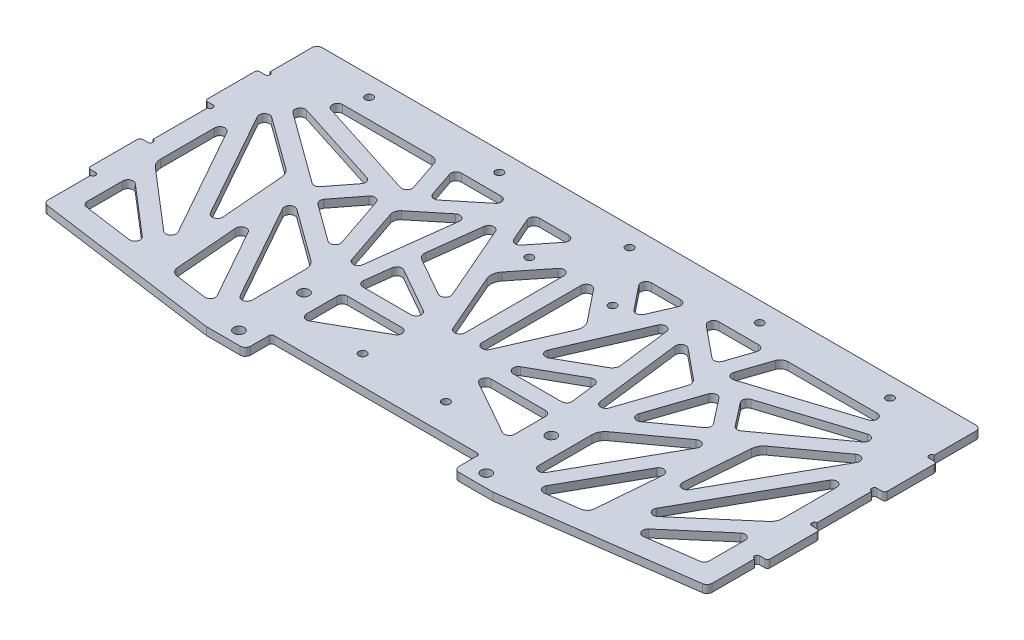
SolidWorks part; units mm, degrees
material "Thornel Mat VMA"
ref_plane "前视基准面" through (0, 0, 0) normal (0, 0, 1) x (1, 0, 0)
ref_plane "上视基准面" through (0, 0, 0) normal (0, 1, 0) x (1, 0, 0)
ref_plane "右视基准面" through (0, 0, 0) normal (1, 0, 0) x (0, 0, -1)
sketch "草图1" plane through (0, 0, 0) normal (0, 1, 0) x (1, 0, 0)
  line L0 (-47.5, 20) -> (-47.5, -10) construction
  line L1 (-55, -10) -> (-127.5, 0)
  line L3 (-55, -10) -> (-40, -10)
  line L5 (-127.5, 105) -> (127.5, 105)
  line L6 (-127.5, 85) -> (-127.5, 105)
  line L11 (0, -1.65) -> (0, 1.65) construction
  line L12 (55, -10) -> (40, -10)
  line L14 (130.5, 85) -> (130.5, 65)
  line L15 (127.5, 65) -> (130.5, 65)
  line L16 (127.5, 85) -> (130.5, 85)
  line L17 (127.5, 85) -> (127.5, 105)
  line L18 (127.5, 0) -> (127.5, 20)
  line L19 (55, -10) -> (127.5, 0)
  line L20 (-40, -10) -> (-40, 0)
  line L21 (-40, 0) -> (40, 0)
  line L22 (40, -10) -> (40, 0)
  line L23 (127.5, 40) -> (127.5, 65)
  line L24 (127.5, 40) -> (130.5, 40)
  line L26 (127.5, 20) -> (130.5, 20)
  line L27 (130.5, 40) -> (130.5, 20)
  line L28 (-127.5, 0) -> (-127.5, 20)
  line L29 (-130.5, 40) -> (-130.5, 20)
  line L30 (-127.5, 20) -> (-130.5, 20)
  line L31 (-127.5, 40) -> (-130.5, 40)
  line L32 (-127.5, 40) -> (-127.5, 65)
  line L33 (-127.5, 85) -> (-130.5, 85)
  line L34 (-127.5, 65) -> (-130.5, 65)
  line L35 (-130.5, 85) -> (-130.5, 65)
  line L37 (-16, 75) -> (16, 75) construction
  line L38 (-16, 75) -> (-16, 11) construction
  line L39 (-16, 11) -> (16, 11) construction
  line L40 (16, 75) -> (16, 11) construction
  circle A0 centre (-47.5, 20) radius 2
  circle A1 centre (-47.5, -5) radius 2
  circle A2 centre (47.5, 20) radius 2
  circle A3 centre (47.5, -5) radius 2
  circle A4 centre (-16, 75) radius 1.5
  circle A5 centre (-16, 11) radius 1.5
  circle A6 centre (16, 11) radius 1.5
  circle A7 centre (16, 75) radius 1.5
  circle A8 centre (-100, 97.5) radius 1.5
  circle A9 centre (-50, 97.5) radius 1.5
  circle A10 centre (0, 97.5) radius 1.5
  circle A11 centre (50, 97.5) radius 1.5
  circle A12 centre (100, 97.5) radius 1.5
  point P58 (0, 105)
  dimension "D4" = 10
  dimension "D5" = 4
  dimension "D6" = 25
  dimension "D2" = 5
  dimension "D15" = 3
  dimension "D16" = 30
  dimension "D17" = 3
  dimension "D19" = 50
  dimension "D20" = 7.5
  dimension "D1" = 115
  dimension "D3" = 80
  dimension "D7" = 255
  dimension "D8" = 3
  dimension "D9" = 20
  dimension "D10" = 15
  dimension "D11" = 20
  dimension "D12" = 25
  dimension "D13" = 64
  dimension "D14" = 32
  dimension "D18" = 5
extrude "凸台-拉伸1" add sketch "草图1" along normal blind 3
sketch "草图3" plane through (0, 3, 0) normal (0, 1, 0) x (1, 0, 0)
  line L0 (-127.5, 65) -> (-127.5, 40) construction
  line L5 (-127.5, 20) -> (-127.5, 0) construction
  line L6 (-127.5, 105) -> (-127.5, 85) construction
  line L7 (0, -1.65) -> (0, 1.65) construction
  circle A0 centre (-127.5, 64) radius 1
  circle A1 centre (-127.5, 86) radius 1
  circle A2 centre (-127.5, 41) radius 1
  circle A3 centre (-127.5, 19) radius 1
  circle A4 centre (127.5, 19) radius 1
  circle A5 centre (127.5, 41) radius 1
  circle A6 centre (127.5, 86) radius 1
  circle A7 centre (127.5, 64) radius 1
  dimension "D1" = 2
extrude "切除-拉伸1" cut sketch "草图3" against normal blind 3
sketch "草图4" plane through (0, 3, 0) normal (0, 1, 0) x (1, 0, 0)
  line L0 (-119.5, 26.7423) -> (-119.5, 6.9723)
  line L1 (-119.5, 6.9723) -> (-92.0657, 3.1883)
  line L2 (-92.0657, 3.1883) -> (-119.5, 26.7423)
  line L3 (-119.5, 65.3141) -> (-119.5, 34.6503)
  line L4 (-119.5, 34.6503) -> (-86.3285, 6.1705)
  line L5 (-86.3285, 6.1705) -> (-119.5, 65.3141)
  line L6 (-119.5, 77.5796) -> (-87.5063, 20.5361)
  line L8 (-61.2863, -1.0572) -> (-82.8712, 37.4278)
  line L9 (-90.451, 56.45) -> (-119.5, 77.5796)
  line L10 (-127.5, 0) -> (-55, -10) construction
  line L11 (-127.5, 18) -> (-127.5, 0) construction
  line L12 (-60.2447, 72.342) -> (-66.2124, 90)
  line L13 (-84.049, 51.7934) -> (-55, 0)
  line L14 (-55, 0) -> (-55, 30.6638)
  line L15 (-55, 30.6638) -> (-84.049, 51.7934)
  line L16 (-40, -10) -> (-40, 0) construction
  line L17 (-66.2124, 90) -> (-115.441, 90)
  line L18 (-115.441, 90) -> (-60.2447, 72.342)
  line L20 (-119.5, 84.999) -> (-80.849, 56.8851)
  line L21 (-119.5, 84.999) -> (-71.0449, 69.4975)
  line L22 (127.5, 105) -> (-127.5, 105) construction
  line L23 (-71.0449, 69.4975) -> (-80.849, 56.8851)
  line L24 (-87.5063, 20.5361) -> (-90.451, 56.45)
  line L25 (-82.8712, 37.4278) -> (-79.9266, 1.5139)
  line L26 (-64.9588, 67.5505) -> (-75.9944, 53.354)
  line L27 (-75.9944, 53.354) -> (-55, 38.0831)
  line L28 (-40, 0) -> (40, 0) construction
  line L29 (-79.9266, 1.5139) -> (-61.2863, -1.0572)
  line L30 (-64.9588, 67.5505) -> (-55, 38.0831)
  line L31 (-57.6573, 64.6859) -> (-46.6022, 31.9748)
  line L32 (-57.6573, 64.6859) -> (-40.834, 78.4483)
  line L33 (-46.6022, 31.9748) -> (-40.834, 78.4483)
  line L34 (-59.879, 90) -> (-36.1891, 90)
  line L35 (-36.1891, 90) -> (-54.748, 74.8177)
  line L36 (-54.748, 74.8177) -> (-59.879, 90)
  line L37 (-34.1047, 83.9533) -> (-37.7399, 54.6654)
  line L38 (-37.7399, 54.6654) -> (-16.0477, 42.3703)
  line L39 (-16.0477, 42.3703) -> (-34.1047, 83.9533)
  line L40 (-40, 27.2219) -> (-40, 10)
  line L41 (-40, 10) -> (-9.4696, 27.2219)
  line L42 (-9.4696, 27.2219) -> (-40, 27.2219)
  line L43 (-38.5396, 48.2219) -> (-40.4014, 33.2219)
  line L44 (-40.4014, 33.2219) -> (-12.075, 33.2219)
  line L45 (-12.075, 33.2219) -> (-38.5396, 48.2219)
  line L46 (-30.1891, 90) -> (-11.7085, 90)
  line L49 (-30.1891, 90) -> (-23.6755, 75)
  line L50 (-23.6755, 75) -> (-11.7085, 90)
  line L51 (-3.2649, 81.3419) -> (-18.2649, 62.5402)
  line L52 (-18.2649, 62.5402) -> (-3.2649, 27.9971)
  line L53 (-3.2649, 27.9971) -> (-3.2649, 81.3419)
  line L54 (0, -1.65) -> (0, 1.65) construction
  line L55 (3.2649, 27.9971) -> (3.2649, 81.3419)
  line L56 (18.2649, 62.5402) -> (3.2649, 27.9971)
  line L57 (3.2649, 81.3419) -> (18.2649, 62.5402)
  line L58 (23.6755, 75) -> (11.7085, 90)
  line L59 (30.1891, 90) -> (23.6755, 75)
  line L60 (30.1891, 90) -> (11.7085, 90)
  line L61 (12.075, 33.2219) -> (38.5396, 48.2219)
  line L62 (40.4014, 33.2219) -> (12.075, 33.2219)
  line L63 (38.5396, 48.2219) -> (40.4014, 33.2219)
  line L64 (9.4696, 27.2219) -> (40, 27.2219)
  line L65 (40, 10) -> (9.4696, 27.2219)
  line L66 (40, 27.2219) -> (40, 10)
  line L67 (16.0477, 42.3703) -> (34.1047, 83.9533)
  line L68 (37.7399, 54.6654) -> (16.0477, 42.3703)
  line L69 (34.1047, 83.9533) -> (37.7399, 54.6654)
  line L70 (54.748, 74.8177) -> (59.879, 90)
  line L71 (36.1891, 90) -> (54.748, 74.8177)
  line L72 (59.879, 90) -> (36.1891, 90)
  line L73 (46.6022, 31.9748) -> (40.834, 78.4483)
  line L74 (57.6573, 64.6859) -> (40.834, 78.4483)
  line L75 (57.6573, 64.6859) -> (46.6022, 31.9748)
  line L76 (64.9588, 67.5505) -> (55, 38.0831)
  line L77 (79.9266, 1.5139) -> (61.2863, -1.0572)
  line L78 (75.9944, 53.354) -> (55, 38.0831)
  line L79 (64.9588, 67.5505) -> (75.9944, 53.354)
  line L80 (82.8712, 37.4278) -> (79.9266, 1.5139)
  line L81 (87.5063, 20.5361) -> (90.451, 56.45)
  line L82 (71.0449, 69.4975) -> (80.849, 56.8851)
  line L83 (119.5, 84.999) -> (71.0449, 69.4975)
  line L84 (119.5, 84.999) -> (80.849, 56.8851)
  line L85 (115.441, 90) -> (60.2447, 72.342)
  line L86 (66.2124, 90) -> (115.441, 90)
  line L87 (55, 30.6638) -> (84.049, 51.7934)
  line L88 (55, 0) -> (55, 30.6638)
  line L89 (84.049, 51.7934) -> (55, 0)
  line L90 (60.2447, 72.342) -> (66.2124, 90)
  line L91 (90.451, 56.45) -> (119.5, 77.5796)
  line L92 (61.2863, -1.0572) -> (82.8712, 37.4278)
  line L93 (119.5, 77.5796) -> (87.5063, 20.5361)
  line L94 (86.3285, 6.1705) -> (119.5, 65.3141)
  line L95 (119.5, 34.6503) -> (86.3285, 6.1705)
  line L96 (119.5, 65.3141) -> (119.5, 34.6503)
  line L97 (92.0657, 3.1883) -> (119.5, 26.7423)
  line L98 (119.5, 6.9723) -> (92.0657, 3.1883)
  line L99 (119.5, 26.7423) -> (119.5, 6.9723)
  circle A0 centre (-16, 75) radius 1.5 construction
  dimension "D36" = 6
  dimension "D1" = 8
  dimension "D2" = 8
  dimension "D3" = 6
  dimension "D4" = 15
  dimension "D5" = 6
  dimension "D6" = 6
  dimension "D7" = 15
  dimension "D8" = 15
  dimension "D9" = 15
  dimension "D10" = 15
  dimension "D11" = 6
  dimension "D12" = 6
  dimension "D13" = 15
  dimension "D14" = 15
  dimension "D15" = 6
  dimension "D16" = 15
  dimension "D17" = 15
  dimension "D18" = 6
  dimension "D19" = 15
  dimension "D20" = 6
  dimension "D21" = 6
  dimension "D22" = 6
  dimension "D23" = 15
  dimension "D24" = 15
  dimension "D25" = 6
  dimension "D26" = 15
  dimension "D27" = 6
  dimension "D28" = 6
  dimension "D29" = 15
  dimension "D30" = 15
  dimension "D31" = 10
  dimension "D32" = 6
  dimension "D33" = 15
  dimension "D34" = 6
  dimension "D35" = 6
  dimension "D37" = 6
  dimension "D38" = 15
extrude "切除-拉伸2" cut sketch "草图4" against normal through all
fillet "圆角1" radius 1 10 edges at (130.5, 1.5, -20) (130.5, 1.5, -40) (130.5, 1.5, -65) (130.5, 1.5, -85) (-130.5, 1.5, -20) (-130.5, 1.5, -40) (-130.5, 1.5, -65) (-130.5, 1.5, -85) (40, 1.5, 0) (-40, 1.5, 0)
fillet "圆角3" radius 5 8 edges at (90.451, 1.5, -56.45) (119.5, 1.5, -34.6503) (55, 1.5, -30.6638) (18.2649, 1.5, -62.5402) (-18.2649, 1.5, -62.5402) (-119.5, 1.5, -34.6503) (-55, 1.5, -30.6638) (-90.451, 1.5, -56.45)
fillet "圆角4" radius 3 8 edges at (79.9266, 1.5, -1.5139) (-79.9266, 1.5, -1.5139) (66.2124, 1.5, -90) (57.6573, 1.5, -64.6859) (37.7399, 1.5, -54.6654) (-37.7399, 1.5, -54.6654) (-66.2124, 1.5, -90) (-57.6573, 1.5, -64.6859)
fillet "圆角2" radius 2 80 edges at (127.5, 1.5, -105) (127.5, 1.5, 0) (40, 1.5, 10) (-40, 1.5, 10) (-127.5, 1.5, 0) (-127.5, 1.5, -105) (-119.5, 1.5, -6.9723) (-119.5, 1.5, -26.7423) (-92.0657, 1.5, -3.1883) (55, 1.5, -38.0831) (64.9588, 1.5, -67.5505) (75.9944, 1.5, -53.354) (40.834, 1.5, -78.4483) (46.6022, 1.5, -31.9748) (61.2863, 1.5, 1.0572) (82.8712, 1.5, -37.4278) (119.5, 1.5, -77.5796) (87.5063, 1.5, -20.5361) (38.5396, 1.5, -48.2219) (40.4014, 1.5, -33.2219) (12.075, 1.5, -33.2219) (40, 1.5, -27.2219) (40, 1.5, -10) (9.4696, 1.5, -27.2219) (59.879, 1.5, -90) (54.748, 1.5, -74.8177) (36.1891, 1.5, -90) (34.1047, 1.5, -83.9533) (16.0477, 1.5, -42.3703) (119.5, 1.5, -26.7423) (119.5, 1.5, -6.9723) (92.0657, 1.5, -3.1883) (60.2447, 1.5, -72.342) (115.441, 1.5, -90) (80.849, 1.5, -56.8851) (71.0449, 1.5, -69.4975) (119.5, 1.5, -84.999) (84.049, 1.5, -51.7934) (55, 1.5, 0) (119.5, 1.5, -65.3141) (86.3285, 1.5, -6.1705) (-55, 1.5, 0) (-84.049, 1.5, -51.7934) (-80.849, 1.5, -56.8851) (-119.5, 1.5, -84.999) (-71.0449, 1.5, -69.4975) (-60.2447, 1.5, -72.342) (-115.441, 1.5, -90) (-82.8712, 1.5, -37.4278) (-36.1891, 1.5, -90) (-54.748, 1.5, -74.8177) (-59.879, 1.5, -90) (-40.834, 1.5, -78.4483) (-46.6022, 1.5, -31.9748) (-87.5063, 1.5, -20.5361) (-119.5, 1.5, -77.5796) (-119.5, 1.5, -65.3141) (-86.3285, 1.5, -6.1705) (3.2649, 1.5, -81.3419) (3.2649, 1.5, -27.9971) (11.7085, 1.5, -90) (30.1891, 1.5, -90) (23.6755, 1.5, -75) (-3.2649, 1.5, -81.3419) (-3.2649, 1.5, -27.9971) (-30.1891, 1.5, -90) (-11.7085, 1.5, -90) (-23.6755, 1.5, -75) (-75.9944, 1.5, -53.354) (-64.9588, 1.5, -67.5505) (-55, 1.5, -38.0831) (-34.1047, 1.5, -83.9533) (-16.0477, 1.5, -42.3703) (-40.4014, 1.5, -33.2219) (-38.5396, 1.5, -48.2219) (-12.075, 1.5, -33.2219) (-40, 1.5, -10) (-40, 1.5, -27.2219) (-9.4696, 1.5, -27.2219) (-61.2863, 1.5, 1.0572)
